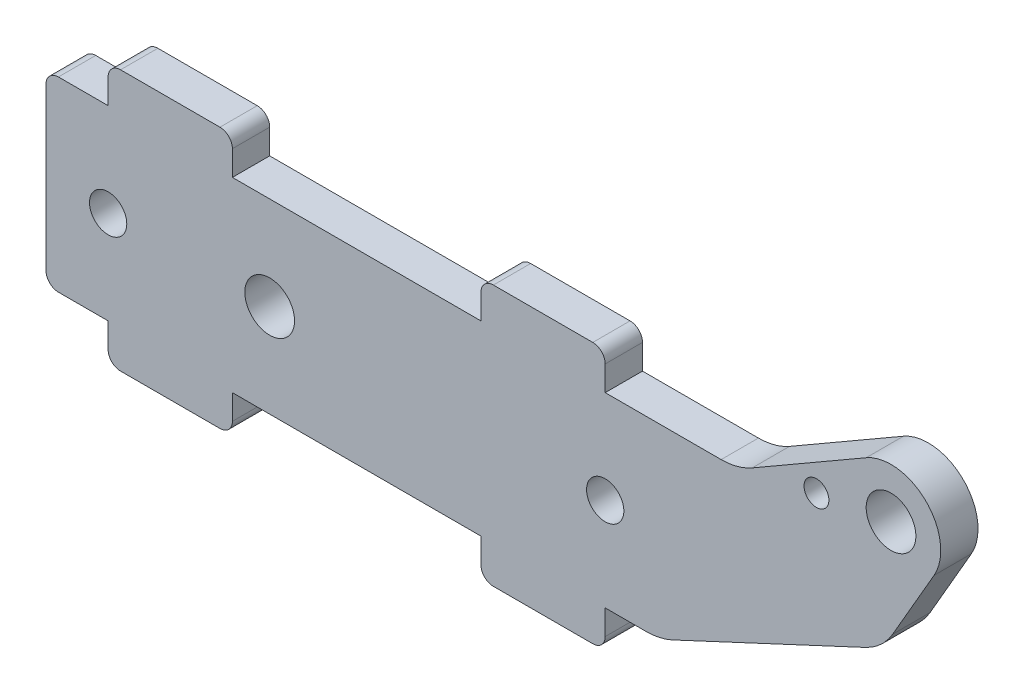
SolidWorks part; units mm, degrees
material "Thornel Mat VMA"
ref_plane "前视基准面" through (0, 0, 0) normal (0, 0, 1) x (1, 0, 0)
ref_plane "上视基准面" through (0, 0, 0) normal (0, 1, 0) x (1, 0, 0)
ref_plane "右视基准面" through (0, 0, 0) normal (1, 0, 0) x (0, 0, -1)
sketch "草图1" plane through (0, 0, 0) normal (0, 0, 1) x (1, 0, 0)
  line L0 (0, 0) -> (45, 0) construction
  line L1 (0, 7.5) -> (5, 7.5)
  line L2 (5, 7.5) -> (5, 10.5)
  line L3 (5, 10.5) -> (15, 10.5)
  line L4 (15, 10.5) -> (15, 7.5)
  line L5 (15, 7.5) -> (35, 7.5)
  line L6 (15, -7.5) -> (35, -7.5)
  line L7 (15, -10.5) -> (15, -7.5)
  line L8 (5, -10.5) -> (15, -10.5)
  line L9 (5, -7.5) -> (5, -10.5)
  line L10 (0, -7.5) -> (5, -7.5)
  line L11 (0, 7.5) -> (0, -7.5)
  line L12 (66, 13.4641) -> (56.8301, 8.1699)
  line L13 (35, 7.5) -> (35, 10.5)
  line L14 (35, 10.5) -> (45, 10.5)
  line L15 (45, 10.5) -> (45, 7.5)
  line L16 (45, 7.5) -> (54.3301, 7.5)
  line L17 (45, -10.5) -> (45, -7.5)
  line L18 (35, -10.5) -> (45, -10.5)
  line L19 (35, -7.5) -> (35, -10.5)
  line L20 (45, -7.5) -> (48.2923, -7.5)
  line L21 (68.1349, 2.2336) -> (71.4641, 8)
  line L22 (50.4054, -7.0315) -> (65.9178, 0.202)
  circle A0 centre (68, 10) radius 2
  arc A1 (71.4641, 8) -> (66, 13.4641) centre (68, 10) ccw
  arc A2 (56.8301, 8.1699) -> (54.3301, 7.5) centre (54.3301, 12.5) cw
  arc A3 (50.4054, -7.0315) -> (48.2923, -7.5) centre (48.2923, -2.5) cw
  circle A4 centre (5, 0) radius 1.5
  circle A5 centre (45, 0) radius 1.5
  arc A6 (65.9178, 0.202) -> (68.1349, 2.2336) centre (63.8047, 4.7336) ccw
  circle A7 centre (18, 0) radius 2
  circle A8 centre (62, 9) radius 1
  point P41 (45.6209, 0)
  dimension "D6" = 10
  dimension "D5" = 23
  dimension "D10" = 8
  dimension "D13" = 30
  dimension "D14" = 5
  dimension "D15" = 10
  dimension "D16" = 5
  dimension "D17" = 3
  dimension "D12" = 5
  dimension "D7" = 4
  dimension "D20" = 5
  dimension "D21" = 4
  dimension "D22" = 3
  dimension "D23" = 2
  dimension "D24" = 9
  dimension "D25" = 17
  dimension "D1" = 15
  dimension "D2" = 3
  dimension "D3" = 5
  dimension "D4" = 10
  dimension "D8" = 20
  dimension "D9" = 10
  dimension "D11" = 60
  dimension "D18" = 8
  dimension "D19" = 25
extrude "凸台-拉伸1" add sketch "草图1" along normal blind 3
fillet "圆角1" radius 1 10 edges at (45, -10.5, 1.5) (35, -10.5, 1.5) (15, -10.5, 1.5) (0, -7.5, 1.5) (5, -10.5, 1.5) (5, 10.5, 1.5) (15, 10.5, 1.5) (35, 10.5, 1.5) (45, 10.5, 1.5) (0, 7.5, 1.5)
